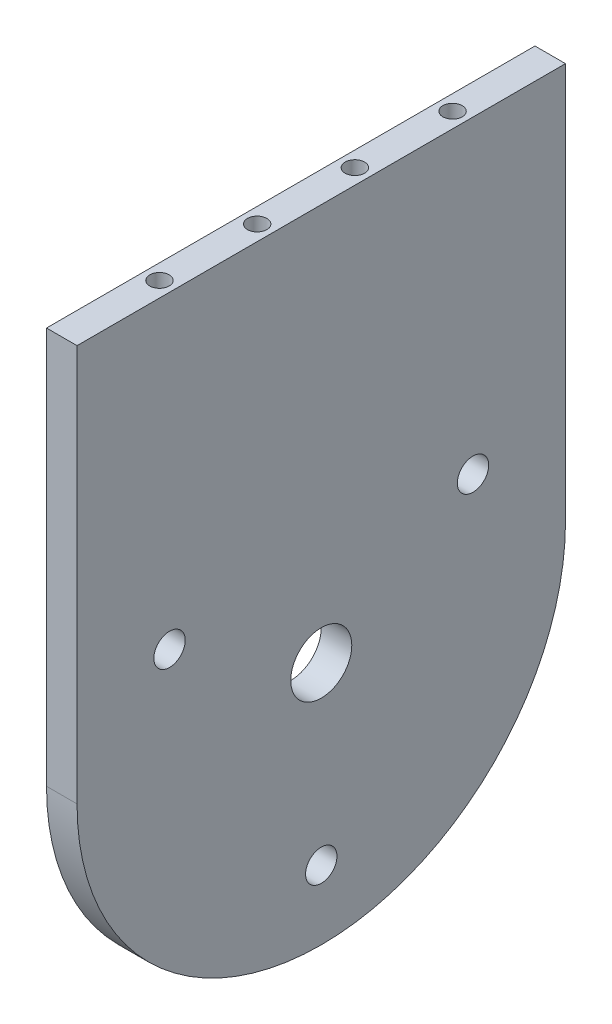
SolidWorks part; units mm, degrees
ref_plane "Front Plane" through (0, 0, 0) normal (0, 0, 1) x (1, 0, 0)
ref_plane "Top Plane" through (0, 0, 0) normal (0, 1, 0) x (1, 0, 0)
ref_plane "Right Plane" through (0, 0, 0) normal (1, 0, 0) x (0, 0, -1)
sketch "Sketch2" plane through (0, 0, 0) normal (1, 0, 0) x (0, 0, -1)
  line L0 (-50.8, -82.55) -> (50.8, -82.55) construction
  line L1 (-50.8, 0) -> (50.8, 0)
  line L2 (-50.8, 0) -> (-50.8, -82.55)
  line L3 (-50.8, -152.4) -> (50.8, -152.4) construction
  line L4 (50.8, 0) -> (50.8, -82.55)
  line L5 (-50.8, -152.4) -> (-50.8, -82.55) construction
  line L6 (50.8, -152.4) -> (50.8, -82.55) construction
  circle A0 centre (0, -82.55) radius 6.35
  arc A1 (-50.8, -82.55) -> (50.8, -82.55) centre (0, -82.55) ccw
  dimension "D1" = 12.7
  dimension "D2" = 69.85
  dimension "D5" = 101.6
  dimension "D6" = 152.4
extrude "Boss-Extrude1" add sketch "Sketch2" along normal mid plane 6.35
hole_wizard "1/4 Clearance Hole1" positions "Sketch4" profile "Sketch3" hole size "1/4" standard "ANSI Inch" end condition through all
sketch "Sketch4" plane through (3.175, 0, 0) normal (1, 0, 0) x (0, 0, -1)
  line L0 (-31.5614, -64.328) -> (0, -82.55) construction
  line L1 (0, -82.55) -> (31.5614, -64.328) construction
  line L2 (0, -82.55) -> (0, -118.9939) construction
  circle A0 centre (0, -82.55) radius 6.35 construction
  point P0 (-31.5614, -64.328)
  point P2 (31.5614, -64.328)
  point P4 (0, -118.9939)
  dimension "D1" = 63.1227
  dimension "D2" = 120
  dimension "D3" = 120
sketch "Sketch3" plane through (3.175, -64.328, 31.5614) normal (0, 1, 0) x (0, 0, -1)
  line L0 (0, 0) -> (0, 6.35)
  line L1 (0, 6.35) -> (3.2639, 6.35)
  line L2 (3.2639, 6.35) -> (3.2639, 0)
  line L5 (3.2639, 0) -> (0, 0)
  line L11 (0, -6.35) -> (0, 107.95) construction
  dimension "Thru Hole Dia." = 6.5278
  dimension "Thru Hole Depth" = 6.35
hole_wizard "#10-32 Tapped Hole1" positions "Sketch6" profile "Sketch5" tap size "#10-32" standard "ANSI Inch"
sketch "Sketch6" plane through (0, 0, 0) normal (0, 1, 0) x (1, 0, 0)
  line L0 (0, 50.8) -> (0, 30.48) construction
  line L1 (3.175, 50.8) -> (-3.175, 50.8) construction
  line L2 (0, 30.48) -> (0, 10.16) construction
  line L3 (0, 10.16) -> (0, -10.16) construction
  line L4 (0, -10.16) -> (0, -30.48) construction
  line L5 (0, -30.48) -> (0, -50.8) construction
  line L6 (3.175, -50.8) -> (-3.175, -50.8) construction
  point P0 (0, 30.48)
  point P2 (0, 10.16)
  point P4 (0, -10.16)
  point P6 (0, -30.48)
cosmetic thread "Hole Thread1" parameters "D1"=5.588, "D2"=4.826
cosmetic thread "Hole Thread2" parameters "D1"=5.588, "D2"=4.826
cosmetic thread "Hole Thread3" parameters "D1"=5.588, "D2"=4.826
cosmetic thread "Hole Thread4" parameters "D1"=5.588, "D2"=4.826
sketch "Sketch5" plane through (0, 0, -30.48) normal (1, 0, 0) x (0, 0, 1)
  line L0 (0, 0) -> (0, 13.9133)
  line L1 (0, 13.9133) -> (2.0193, 12.7)
  line L2 (2.0193, 12.7) -> (2.0193, 0)
  line L5 (2.0193, 0) -> (0, 0)
  line L10 (0, 13.9133) -> (-2.0193, 12.7) construction
  line L11 (0, -6.35) -> (0, 107.95) construction
  dimension "Tap Drill Dia." = 4.0386
  dimension "Tap Drill Depth" = 12.7
  dimension "Drill Angle" = 118
